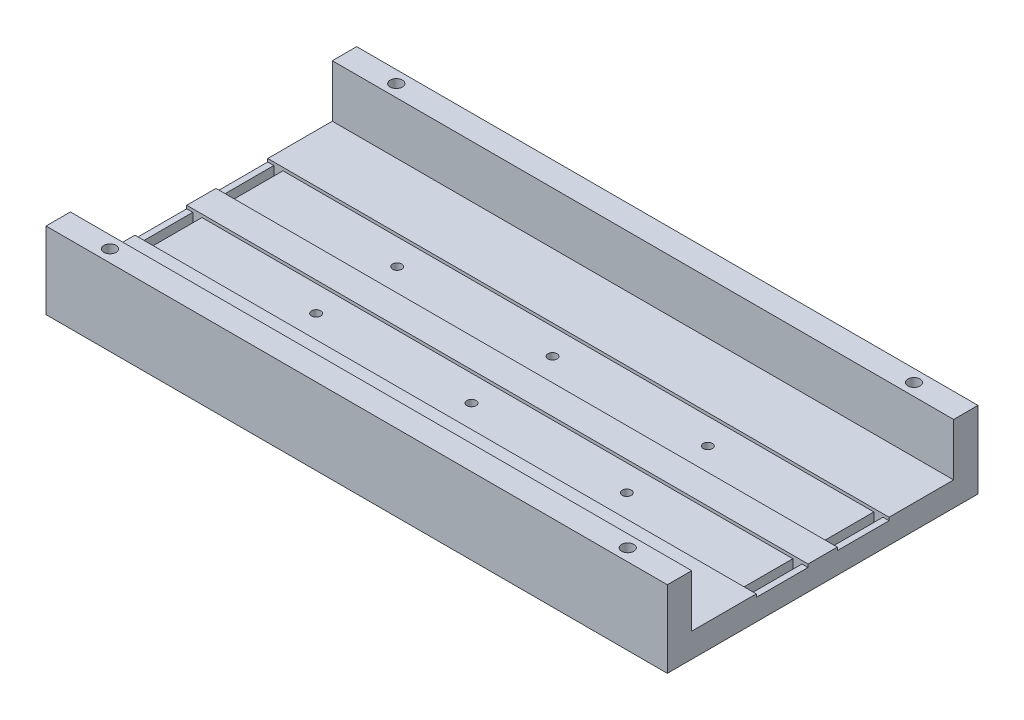
SolidWorks part; units mm, degrees
ref_plane "Front Plane" through (0, 0, 0) normal (0, 0, 1) x (1, 0, 0)
ref_plane "Top Plane" through (0, 0, 0) normal (0, 1, 0) x (1, 0, 0)
ref_plane "Right Plane" through (0, 0, 0) normal (1, 0, 0) x (0, 0, -1)
sketch "Sketch1" plane through (0, 0, 0) normal (0, 1, 0) x (1, 0, 0)
  line L1 (0, 0) -> (102, 0)
  line L2 (0, 0) -> (0, 51)
  line L3 (0, 51) -> (102, 51)
  line L4 (102, 0) -> (102, 51)
  dimension "D1" = 102
  dimension "D2" = 51
extrude "Boss-Extrude2" add sketch "Sketch1" along normal blind 4
sketch "Sketch2" plane through (0, 4, 0) normal (0, 1, 0) x (1, 0, 0)
  line L0 (102, 0) -> (102, 51) construction
  line L1 (0, 51) -> (102, 51)
  line L2 (0, 51) -> (0, 47)
  line L3 (0, 47) -> (102, 47)
  line L4 (102, 51) -> (102, 47)
  line L5 (0, 51) -> (0, 0) construction
  line L6 (102, 0) -> (0, 0)
  line L7 (102, 0) -> (102, 4)
  line L8 (102, 4) -> (0, 4)
  line L9 (0, 0) -> (0, 4)
  dimension "D1" = 4
  dimension "D2" = 4
extrude "Boss-Extrude3" add sketch "Sketch2" along normal blind 8.6
sketch "Sketch3" plane through (0, 4, 0) normal (0, 1, 0) x (1, 0, 0)
  line L0 (0, 47) -> (0, 4) construction
  line L1 (0, 14.6) -> (102, 14.6)
  line L2 (0, 14.6) -> (0, 23.1)
  line L3 (0, 23.1) -> (102, 23.1)
  line L4 (102, 14.6) -> (102, 23.1)
  line L5 (102, 4) -> (102, 47) construction
  line L7 (0, 27.9) -> (102, 27.9)
  line L8 (0, 27.9) -> (0, 36.4)
  line L9 (0, 36.4) -> (102, 36.4)
  line L10 (102, 27.9) -> (102, 36.4)
  dimension "D1" = 8.5
  dimension "D2" = 8.5
  dimension "D3" = 10.6
  dimension "D4" = 10.6
extrude "Cut-Extrude2" cut sketch "Sketch3" against normal blind 0.5
sketch "Sketch4" plane through (0, 3.5, 0) normal (0, 1, 0) x (1, 0, 0)
  line L0 (102, 14.6) -> (102, 23.1) construction
  line L1 (102, 23.1) -> (0, 23.1) construction
  line L2 (102, 23.1) -> (0, 23.1) construction
  line L3 (0, 23.1) -> (0, 14.6) construction
  line L4 (0, 27.9) -> (102, 27.9) construction
  line L5 (102, 27.9) -> (102, 36.4) construction
  line L6 (102, 36.4) -> (0, 36.4) construction
  line L7 (0, 36.4) -> (0, 27.9) construction
  line L8 (0, 27.9) -> (102, 27.9) construction
  line L9 (0, 14.6) -> (102, 14.6) construction
  line L10 (101, 14.6) -> (99.5, 14.6)
  line L11 (101, 14.6) -> (101, 23.1)
  line L12 (101, 23.1) -> (99.5, 23.1)
  line L13 (99.5, 14.6) -> (99.5, 23.1)
  line L14 (102, 36.4) -> (0, 36.4) construction
  line L15 (101, 27.9) -> (99.5, 27.9)
  line L16 (101, 27.9) -> (101, 36.4)
  line L17 (101, 36.4) -> (99.5, 36.4)
  line L18 (99.5, 27.9) -> (99.5, 36.4)
  line L20 (2.5, 14.6) -> (1, 14.6)
  line L21 (2.5, 14.6) -> (2.5, 23.1)
  line L22 (2.5, 23.1) -> (1, 23.1)
  line L23 (1, 14.6) -> (1, 23.1)
  line L24 (1, 27.9) -> (2.5, 27.9)
  line L25 (1, 27.9) -> (1, 36.4)
  line L26 (1, 36.4) -> (2.5, 36.4)
  line L27 (2.5, 27.9) -> (2.5, 36.4)
  circle A0 centre (51, 18.85) radius 0.75
  circle A1 centre (76.5, 18.85) radius 0.75
  circle A2 centre (25.5, 18.85) radius 0.75
  circle A3 centre (76.5, 32.15) radius 0.75
  circle A4 centre (51, 32.15) radius 0.75
  circle A5 centre (25.5, 32.15) radius 0.75
  point P8 (102, 18.85)
  point P15 (0, 18.85)
  point P22 (51, 36.4)
  dimension "D3" = 1.5
  dimension "D5" = 1.5
  dimension "D8" = 1.5
  dimension "D11" = 1.5
  dimension "D13" = 1.5
  dimension "D16" = 1.5
  dimension "D1" = 51
  dimension "D2" = 4.25
  dimension "D4" = 25.5
  dimension "D6" = 4.25
  dimension "D7" = 25.5
  dimension "D9" = 4.25
  dimension "D10" = 4.25
  dimension "D12" = 25.5
  dimension "D14" = 4.25
  dimension "D15" = 51
  dimension "D17" = 4.25
  dimension "D18" = 25.5
  dimension "D19" = 8.5
  dimension "D20" = 1
  dimension "D21" = 1.5
  dimension "D22" = 8.5
  dimension "D23" = 1
  dimension "D24" = 1.5
  dimension "D25" = 8.5
  dimension "D26" = 1
  dimension "D27" = 1.5
  dimension "D28" = 1
  dimension "D29" = 1.5
extrude "Cut-Extrude4" cut sketch "Sketch4" against normal blind 10
sketch "Sketch6" plane through (0, 12.6, 0) normal (0, 1, 0) x (1, 0, 0)
  line L0 (102, 0) -> (102, 4) construction
  line L1 (0, 4) -> (0, 0) construction
  line L2 (102, 4) -> (0, 4) construction
  line L3 (0, 47) -> (102, 47) construction
  line L4 (102, 47) -> (102, 51) construction
  line L5 (0, 51) -> (0, 47) construction
  circle A0 centre (93.5, 2) radius 1
  circle A1 centre (8.5, 2) radius 1
  circle A2 centre (93.5, 49) radius 1
  circle A3 centre (8.5, 49) radius 1
  point P6 (102, 2)
  point P21 (0, 49)
  dimension "D1" = 2
  dimension "D3" = 2
  dimension "D7" = 2
  dimension "D10" = 2
  dimension "D2" = 8.5
  dimension "D4" = 8.5
  dimension "D5" = 2
  dimension "D6" = 2
  dimension "D8" = 2
  dimension "D9" = 8.5
  dimension "D11" = 8.5
  dimension "D12" = 2
extrude "Cut-Extrude5" cut sketch "Sketch6" against normal blind 15
